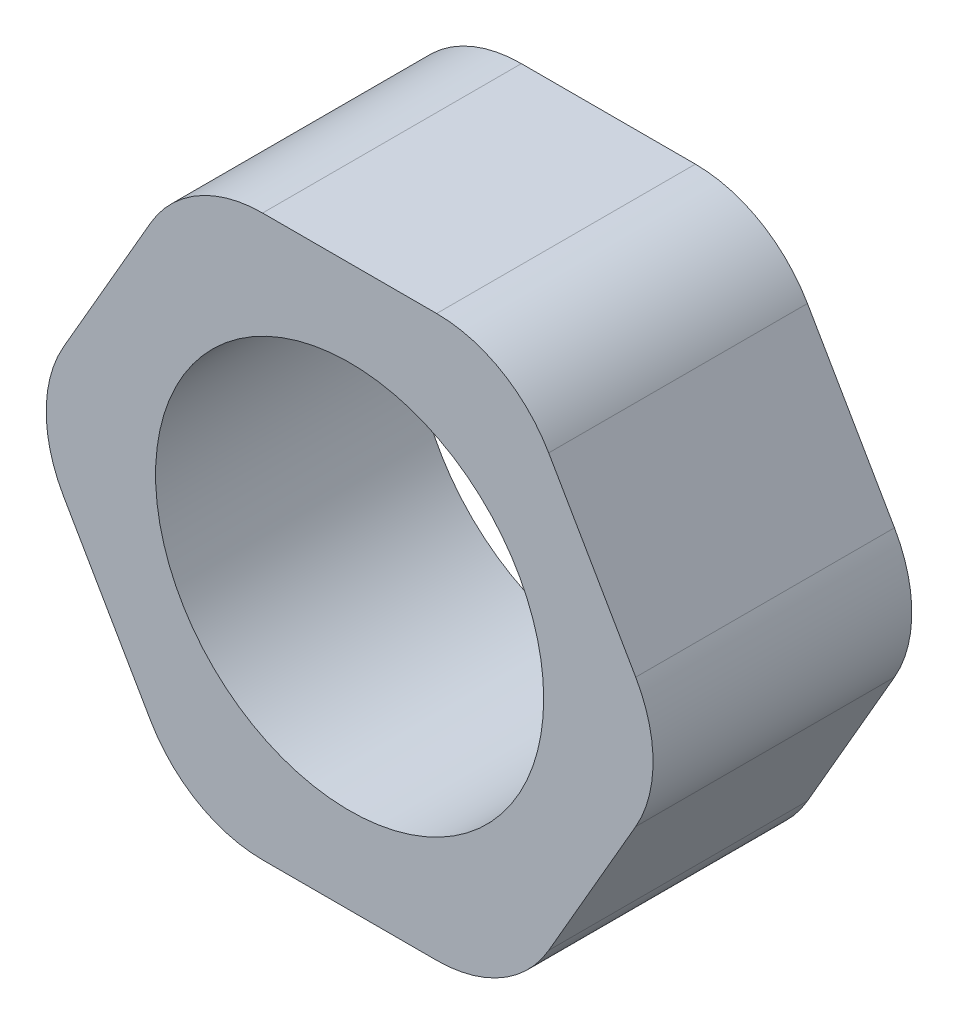
SolidWorks part; units mm, degrees
ref_plane "Alzado" through (0, 0, 0) normal (0, 0, 1) x (1, 0, 0)
ref_plane "Planta" through (0, 0, 0) normal (0, 1, 0) x (1, 0, 0)
ref_plane "Vista lateral" through (0, 0, 0) normal (1, 0, 0) x (0, 0, -1)
sketch "Croquis1" plane through (0, 0, 0) normal (0, 0, 1) x (1, 0, 0)
  line L0 (-2.5, 0) -> (2.5, 0) construction
  line L1 (1.25, 2.1651) -> (-1.25, 2.1651)
  line L2 (-1.25, 2.1651) -> (-2.5, 0)
  line L3 (-2.5, 0) -> (-1.25, -2.1651)
  line L4 (-1.25, -2.1651) -> (1.25, -2.1651)
  line L5 (1.25, -2.1651) -> (2.5, 0)
  line L6 (2.5, 0) -> (1.25, 2.1651)
  circle A0 centre (0, 0) radius 1.5
  circle A1 centre (0, 0) radius 2.5 construction
  dimension "D1" = 3
  dimension "D2" = 5
extrude "Saliente-Extruir1" add sketch "Croquis1" along normal blind 2
fillet "Redondeo1" radius 1 6 edges at (2.5, 0, 1) (1.25, -2.1651, 1) (-1.25, -2.1651, 1) (-2.5, 0, 1) (-1.25, 2.1651, 1) (1.25, 2.1651, 1)
